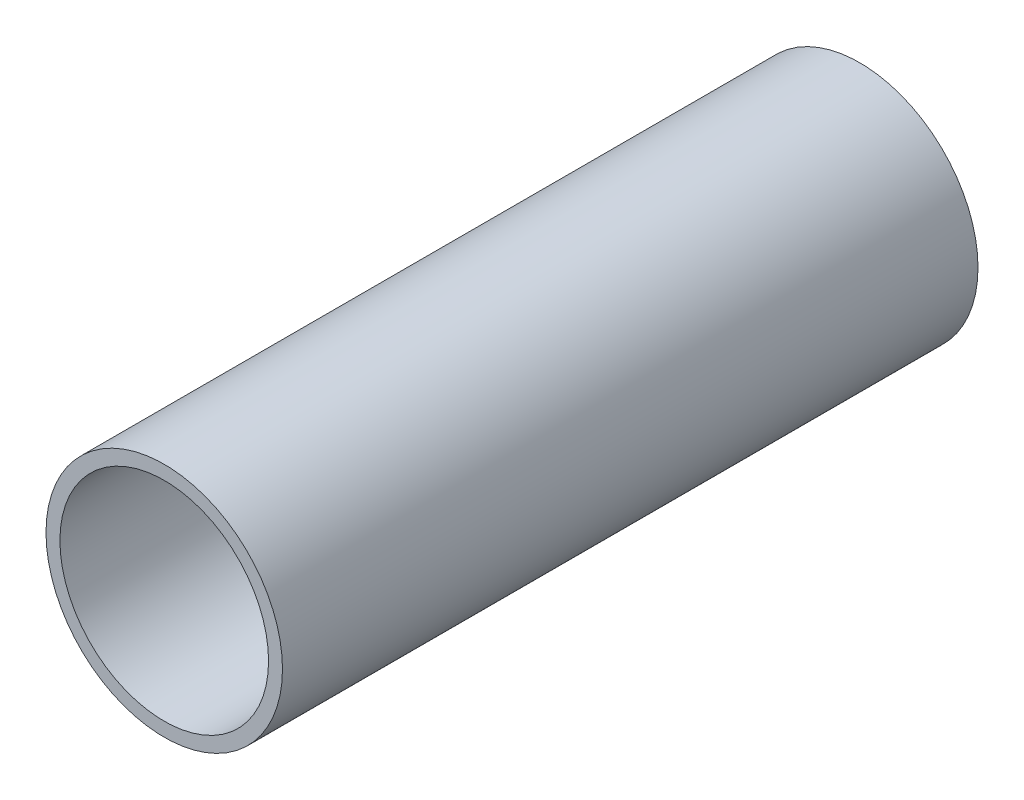
SolidWorks part; units mm, degrees
ref_plane "Front Plane" through (0, 0, 0) normal (0, 0, 1) x (1, 0, 0)
ref_plane "Top Plane" through (0, 0, 0) normal (0, 1, 0) x (1, 0, 0)
ref_plane "Right Plane" through (0, 0, 0) normal (1, 0, 0) x (0, 0, -1)
sketch "Sketch1" plane through (0, 0, 0) normal (0, 0, 1) x (1, 0, 0)
  circle A0 centre (0, 0) radius 15
  circle A1 centre (0, 0) radius 17
  dimension "D1" = 30
  dimension "D2" = 34
extrude "Boss-Extrude1" add sketch "Sketch1" along normal blind 100
